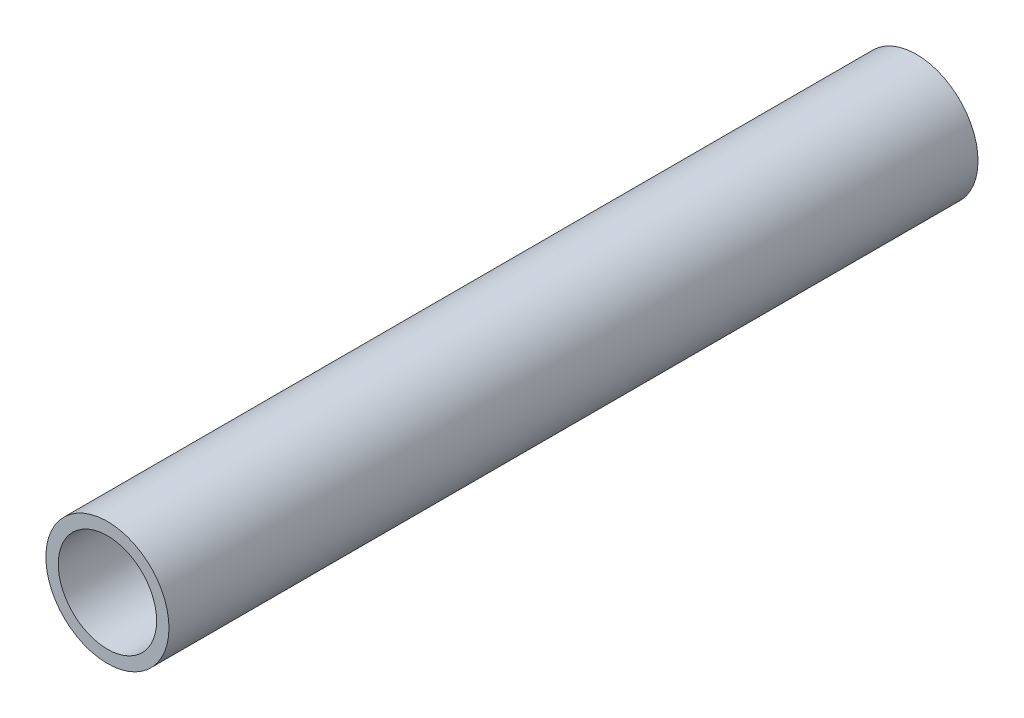
SolidWorks part; units mm, degrees
material "PVC Rígido"
ref_plane "Alzado" through (0, 0, 0) normal (0, 0, 1) x (1, 0, 0)
ref_plane "Planta" through (0, 0, 0) normal (0, 1, 0) x (1, 0, 0)
ref_plane "Vista lateral" through (0, 0, 0) normal (1, 0, 0) x (0, 0, -1)
sketch "Croquis1" plane through (0, 0, 0) normal (0, 0, 1) x (1, 0, 0)
  circle A0 centre (0, 0) radius 10.65
  circle A1 centre (0, 0) radius 8.51
  dimension "D1" = 21.3
  dimension "D2" = 17.02
extrude "Saliente-Extruir1" add sketch "Croquis1" along normal blind 140
